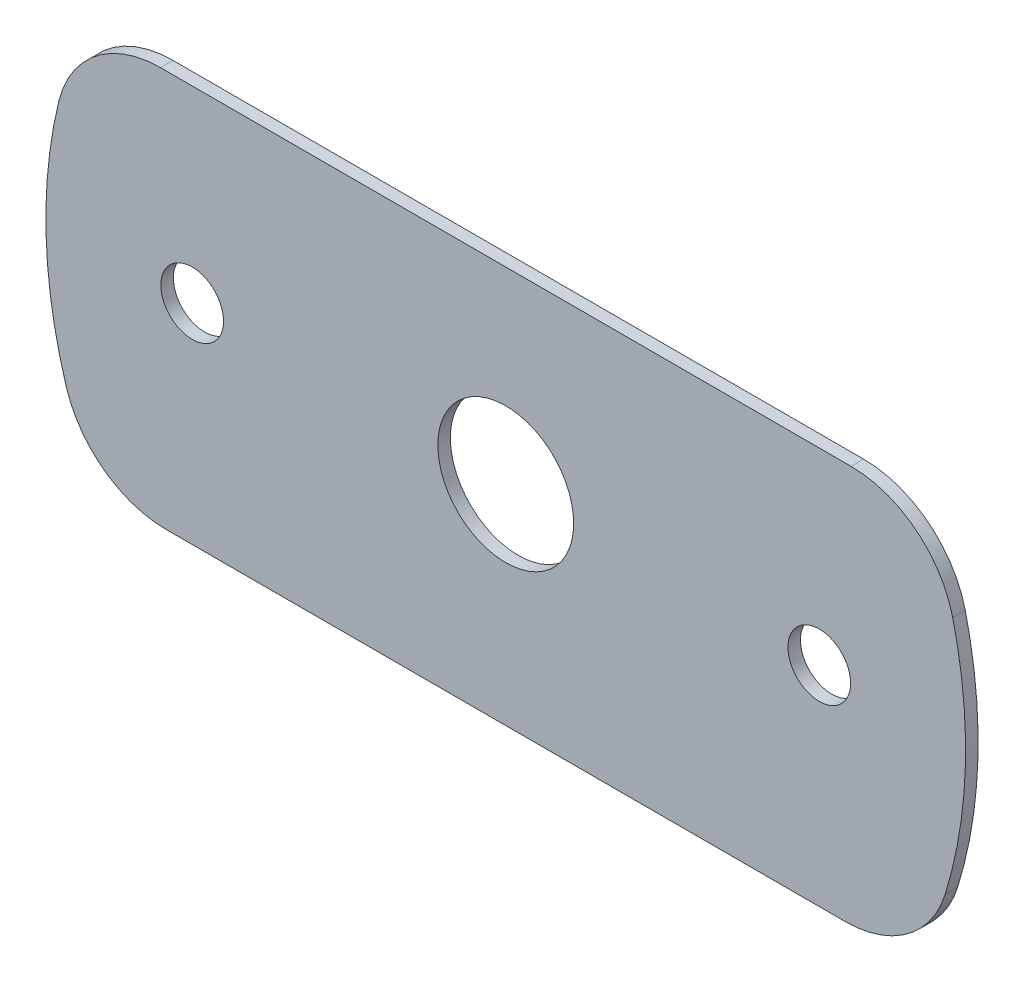
SolidWorks part; units mm, degrees
ref_plane "Спереди" through (0, 0, 0) normal (0, 0, 1) x (1, 0, 0)
ref_plane "Сверху" through (0, 0, 0) normal (0, 1, 0) x (1, 0, 0)
ref_plane "Справа" through (0, 0, 0) normal (1, 0, 0) x (0, 0, -1)
sketch "Эскиз1" plane through (0, 0, 0) normal (0, 0, 1) x (1, 0, 0)
  circle A0 centre (0, 0) radius 22
  dimension "D1" = 44
extrude "Бобышка-Вытянуть1" add sketch "Эскиз1" along normal blind 0.6
sketch "Эскиз2" plane through (0, 0, 0.6) normal (0, 0, 1) x (1, 0, 0)
  circle A0 centre (0, 0) radius 3.25
  dimension "D1" = 6.5
extrude "Вырез-Вытянуть1" cut sketch "Эскиз2" against normal through all
sketch "Эскиз3" plane through (0, 0, 0.6) normal (0, 0, 1) x (1, 0, 0)
  circle A0 centre (-15, 0) radius 1.5
  circle A1 centre (15, 0) radius 1.5
  dimension "D3" = 3
  dimension "D1" = 0
  dimension "D2" = 15
  dimension "D4" = 2
extrude "Вырез-Вытянуть2" cut sketch "Эскиз3" against normal through all
sketch "Эскиз5" plane through (0, 0, 0.6) normal (0, 0, 1) x (1, 0, 0)
  line L1 (-27.9404, 28.515) -> (28.1564, 28.515)
  line L2 (-27.9404, 28.515) -> (-27.9404, 9)
  line L3 (-27.9404, 9) -> (28.1564, 9)
  line L4 (28.1564, 28.515) -> (28.1564, 9)
  line L5 (-27.9404, -10) -> (28.7325, -10)
  line L6 (-27.9404, -10) -> (-27.9404, -31.6754)
  line L7 (-27.9404, -31.6754) -> (28.7325, -31.6754)
  line L8 (28.7325, -10) -> (28.7325, -31.6754)
  dimension "D1" = 19
  dimension "D2" = 10
extrude "Вырез-Вытянуть4" cut sketch "Эскиз5" against normal through all
fillet "Скругление1" radius 5 4 edges at (20.0749, 9, 0.3) (-20.0749, 9, 0.3) (-19.5959, -10, 0.3) (19.5959, -10, 0.3)
